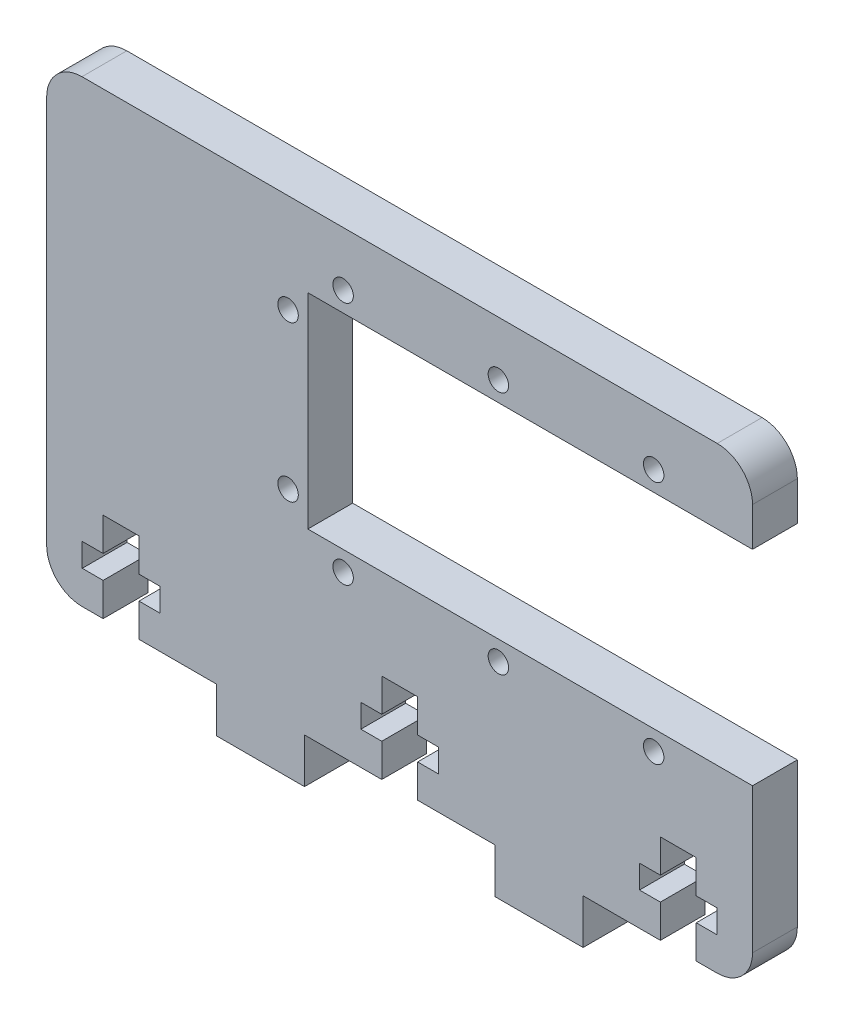
SolidWorks part; units mm, degrees
ref_plane "Front Plane" through (0, 0, 0) normal (0, 0, 1) x (1, 0, 0)
ref_plane "Top Plane" through (0, 0, 0) normal (0, 1, 0) x (1, 0, 0)
ref_plane "Right Plane" through (0, 0, 0) normal (1, 0, 0) x (0, 0, -1)
sketch "Sketch1" plane through (0, 0, 0) normal (0, 0, 1) x (1, 0, 0)
  line L0 (0, 32.5) -> (100, 32.5) construction
  line L1 (0, 0) -> (100, 0)
  line L2 (0, 0) -> (0, 65)
  line L3 (0, 65) -> (100, 65)
  line L4 (100, 0) -> (100, 65)
  line L5 (92, 65) -> (92, 0) construction
  dimension "D1" = 65
  dimension "D2" = 100
  dimension "D3" = 8
extrude "Boss-Extrude1" add sketch "Sketch1" along normal blind 6.35
hole_wizard "M2.5 Clearance Hole1" positions "Sketch3" profile "Sketch2" hole size "M2.5" standard "ANSI Metric" end condition through all
sketch "Sketch3" plane through (0, 0, 6.35) normal (0, 0, 1) x (1, 0, 0)
  line L0 (100, 40) -> (0, 40) construction
  line L1 (100, 0) -> (100, 65) construction
  line L2 (0, 65) -> (0, 0) construction
  line L4 (82, 65) -> (82, 0) construction
  line L5 (100, 65) -> (0, 65) construction
  line L6 (0, 0) -> (100, 0) construction
  line L8 (100, 57.3) -> (0, 57.3) construction
  line L10 (0, 51) -> (100, 51) construction
  line L11 (100, 22.7) -> (0, 22.7) construction
  line L12 (0, 29) -> (100, 29) construction
  point P23 (86, 57.3)
  point P25 (64, 57.3)
  point P27 (42, 57.3)
  point P31 (34.2, 51)
  point P34 (86, 22.7)
  point P35 (64, 22.7)
  point P36 (42, 22.7)
  point P39 (34.2, 29)
  dimension "D1" = 18
  dimension "D2" = 17.3
  dimension "D3" = 11
  dimension "D4" = 22
  dimension "D5" = 22
  dimension "D6" = 4
  dimension "D7" = 47.8
  dimension "D8" = 25
sketch "Sketch2" plane through (86, 57.3, 6.35) normal (1, 0, 0) x (0, -1, 0)
  line L0 (0, 0) -> (0, 6.35)
  line L1 (0, 6.35) -> (1.45, 6.35)
  line L2 (1.45, 6.35) -> (1.45, 0)
  line L5 (1.45, 0) -> (0, 0)
  line L11 (0, -6.35) -> (0, 107.95) construction
  dimension "Thru Hole Dia." = 2.9
  dimension "Thru Hole Depth" = 6.35
sketch "Sketch4" plane through (0, 0, 6.35) normal (0, 0, 1) x (1, 0, 0)
  line L0 (100, 0) -> (100, 65) construction
  line L1 (100, 25.5) -> (37, 25.5)
  line L2 (100, 25.5) -> (100, 54.5)
  line L3 (100, 54.5) -> (37, 54.5)
  line L4 (37, 25.5) -> (37, 54.5)
  line L5 (100, 40) -> (0, 40) construction
  line L7 (82, 65) -> (82, 0) construction
  line L8 (100, 65) -> (0, 65) construction
  line L9 (0, 0) -> (100, 0) construction
  line L10 (0, 65) -> (0, 0) construction
  line L11 (0, 0) -> (100, 0) construction
  point P16 (37, 40)
  dimension "D1" = 29
  dimension "D2" = 18
  dimension "D3" = 45
  dimension "D4" = 25
  dimension "D5" = 40
extrude "Cut-Extrude1" cut sketch "Sketch4" against normal through all
fillet "Fillet2" radius 5 4 edges at (100, 0, 3.175) (100, 65, 3.175) (0, 65, 3.175) (0, 0, 3.175)
sketch "Sketch5" plane through (0, 0, 6.35) normal (0, 0, 1) x (1, 0, 0)
  line L0 (5, 0) -> (95, 0) construction
  line L1 (63.5, 0) -> (76, 0)
  line L2 (63.5, 0) -> (63.5, -6.35)
  line L3 (63.5, -6.35) -> (76, -6.35)
  line L4 (76, 0) -> (76, -6.35)
  line L5 (100, 5) -> (100, 25.5) construction
  line L7 (24.0258, 0) -> (36.5258, 0)
  line L8 (24.0258, 0) -> (24.0258, -6.35)
  line L9 (24.0258, -6.35) -> (36.5258, -6.35)
  line L10 (36.5258, 0) -> (36.5258, -6.35)
  dimension "D1" = 6.35
  dimension "D2" = 12.5
  dimension "D3" = 24
  dimension "D4" = 12.5
  dimension "D5" = 6.35
  dimension "D6" = 39.4742
extrude "Boss-Extrude2" add sketch "Sketch5" against normal blind 6.35
sketch "Sketch7" plane through (0, 0, 0) normal (0, 0, -1) x (-1, 0, 0)
  line L0 (-50.0129, 12.7) -> (-50.0129, 0) construction
  line L1 (-36.5258, 0) -> (-63.5, 0) construction
  line L2 (-92.0271, 0) -> (-92.0271, 4.699)
  line L3 (-92.0271, 12.7) -> (-86.9471, 12.7)
  line L4 (-52.5529, 0) -> (-52.5529, 4.699)
  line L5 (-52.5529, 12.7) -> (-47.4729, 12.7)
  line L6 (-47.4729, 0) -> (-47.4729, 4.699)
  line L7 (-52.5529, 8.001) -> (-52.5529, 12.7)
  line L8 (-55.512, 8.001) -> (-52.5529, 8.001)
  line L9 (-55.512, 8.001) -> (-55.512, 4.699)
  line L10 (-55.512, 4.699) -> (-52.5529, 4.699)
  line L11 (-44.5138, 8.001) -> (-44.5138, 4.699)
  line L12 (-47.4729, 8.001) -> (-44.5138, 8.001)
  line L13 (-47.4729, 8.001) -> (-47.4729, 12.7)
  line L14 (-47.4729, 4.699) -> (-44.5138, 4.699)
  line L15 (-86.9471, 0) -> (-86.9471, 4.699)
  line L16 (-36.5258, 0) -> (-63.5, 0) construction
  line L17 (-47.4729, 0) -> (-52.5529, 0)
  line L18 (-92.0271, 8.001) -> (-92.0271, 12.7)
  line L19 (-94.9862, 8.001) -> (-92.0271, 8.001)
  line L20 (-94.9862, 8.001) -> (-94.9862, 4.699)
  line L21 (-94.9862, 4.699) -> (-92.0271, 4.699)
  line L22 (-83.988, 8.001) -> (-83.988, 4.699)
  line L23 (-86.9471, 8.001) -> (-83.988, 8.001)
  line L24 (-86.9471, 8.001) -> (-86.9471, 12.7)
  line L25 (-86.9471, 4.699) -> (-83.988, 4.699)
  line L26 (-86.9471, 0) -> (-92.0271, 0)
  line L27 (-89.4871, 12.7) -> (-89.4871, 0) construction
  line L28 (-52.5529, 0) -> (-52.5529, 4.699)
  line L29 (-52.5529, 12.7) -> (-47.4729, 12.7)
  line L30 (-47.4729, 0) -> (-47.4729, 4.699)
  line L31 (-52.5529, 8.001) -> (-52.5529, 12.7)
  line L32 (-55.512, 8.001) -> (-52.5529, 8.001)
  line L33 (-55.512, 8.001) -> (-55.512, 4.699)
  line L34 (-55.512, 4.699) -> (-52.5529, 4.699)
  line L35 (-44.5138, 8.001) -> (-44.5138, 4.699)
  line L36 (-47.4729, 8.001) -> (-44.5138, 8.001)
  line L37 (-47.4729, 8.001) -> (-47.4729, 12.7)
  line L38 (-47.4729, 4.699) -> (-44.5138, 4.699)
  line L39 (-47.4729, 0) -> (-52.5529, 0)
  line L40 (-50.0129, 12.7) -> (-50.0129, 0) construction
  line L41 (-13.0787, 0) -> (-13.0787, 4.699)
  line L42 (-13.0787, 12.7) -> (-7.9987, 12.7)
  line L43 (-7.9987, 0) -> (-7.9987, 4.699)
  line L44 (-13.0787, 8.001) -> (-13.0787, 12.7)
  line L45 (-16.0378, 8.001) -> (-13.0787, 8.001)
  line L46 (-16.0378, 8.001) -> (-16.0378, 4.699)
  line L47 (-16.0378, 4.699) -> (-13.0787, 4.699)
  line L48 (-5.0396, 8.001) -> (-5.0396, 4.699)
  line L49 (-7.9987, 8.001) -> (-5.0396, 8.001)
  line L50 (-7.9987, 8.001) -> (-7.9987, 12.7)
  line L51 (-7.9987, 4.699) -> (-5.0396, 4.699)
  line L52 (-7.9987, 0) -> (-13.0787, 0)
  line L53 (-10.5387, 12.7) -> (-10.5387, 0) construction
  line L54 (-69.75, -6.35) -> (-69.75, 25.5) construction
  line L55 (-63.5, -6.35) -> (-76, -6.35) construction
  line L56 (-5, 0) -> (-24.0258, 0) construction
  line L57 (-37, 25.5) -> (-100, 25.5) construction
  line L58 (-84.75, 0) -> (-84.75, 25.5) construction
  line L59 (-76, 0) -> (-95, 0) construction
  point P8 (-50.0129, 12.7)
  point P28 (-89.4871, 12.7)
  point P43 (-50.0129, 12.7)
  point P58 (-10.5387, 12.7)
  line M13 (-95, 0) -> (-76, 0)
  line M17 (-63.5, 0) -> (-36.5258, 0)
  line M21 (-24.0258, 0) -> (-5, 0)
  dimension "D1" = 12.7
  dimension "D2" = 2
  dimension "D3" = 5.08
  dimension "D4" = 2
  dimension "D5" = 10.9982
  dimension "D6" = 3.302
  dimension "D7" = 15
  dimension "D8" = 4.7371
  dimension "D9" = 19.7371
extrude "Cut-Extrude2" cut sketch "Sketch7" against normal through all contours L15 L25 L22 L23 L24 L3 L18 L19 L20 L21 L2 M13 | L6 L14 L11 L12 L13 L5 L7 L8 L9 L10 L4 M17 | L43 L51 L48 L49 L50 L42 L44 L45 L46 L47 L41 M21
